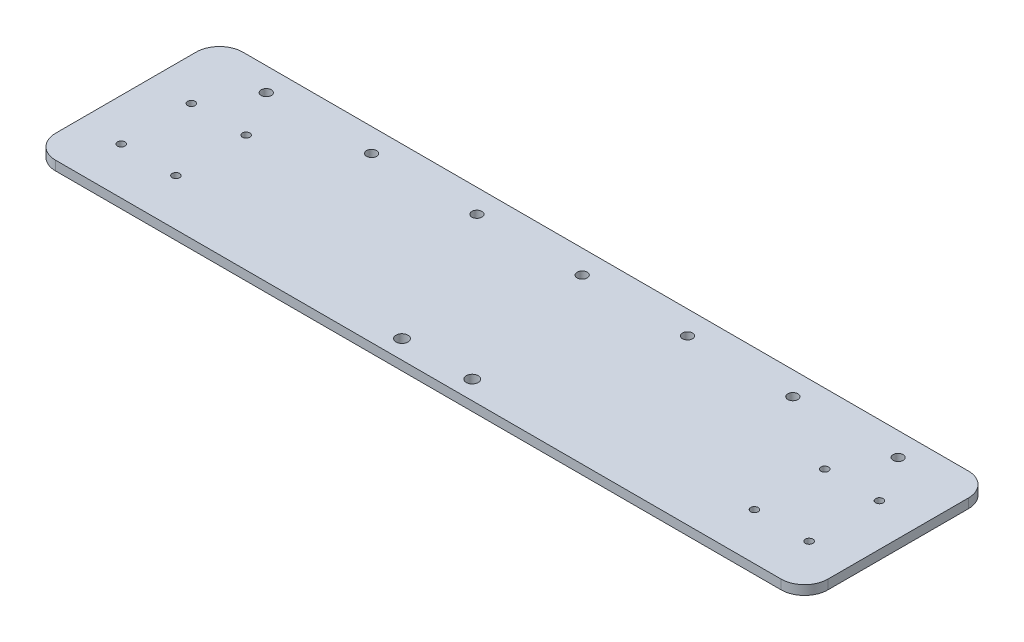
SolidWorks part; units mm, degrees
material "1060 合金"
ref_plane "前视基准面" through (0, 0, 0) normal (0, 0, 1) x (1, 0, 0)
ref_plane "上视基准面" through (0, 0, 0) normal (0, 1, 0) x (1, 0, 0)
ref_plane "右视基准面" through (0, 0, 0) normal (1, 0, 0) x (0, 0, -1)
other "Configuration Table"
sketch "草图2" plane through (0, 0, 0) normal (0, 1, 0) x (1, 0, 0)
  line L0 (0, 57.6658) -> (0, -92.3342) construction
  line L1 (165, 40) -> (-165, 40)
  line L2 (165, 40) -> (165, -40)
  line L4 (-165, 40) -> (-165, -40)
  line L5 (165, 40) -> (-165, -40) construction
  line L6 (165, -40) -> (-165, 40) construction
  line L7 (-15, -32) -> (15, -32) construction
  line L13 (-165, -40) -> (165, -40)
  circle A0 centre (-15, -32) radius 2.55
  circle A1 centre (15, -32) radius 2.55
  point P0 (0, 0)
  point P11 (0, -32)
  dimension "D4" = 5.1
  dimension "D1" = 330
  dimension "D2" = 80
  dimension "D3" = 30
  dimension "D5" = 8
extrude "凸台-拉伸1" add sketch "草图2" along normal blind 4
sketch "草图3" plane through (0, 0, 0) normal (0, 1, 0) x (1, 0, 0)
  line L5 (-165, 40) -> (-165, -40) construction
  line L7 (-147, 10) -> (-123.6, 10) construction
  line L8 (-147, 10) -> (-147, -20) construction
  line L9 (-147, -20) -> (-123.6, -20) construction
  line L10 (-123.6, 10) -> (-123.6, -20) construction
  line L11 (-147, 10) -> (-123.6, -20) construction
  line L12 (-147, -20) -> (-123.6, 10) construction
  line L13 (-165, -40) -> (165, -40) construction
  circle A0 centre (-147, 10) radius 1.6
  circle A1 centre (-147, -20) radius 1.6
  circle A2 centre (-123.6, -20) radius 1.6
  circle A3 centre (-123.6, 10) radius 1.6
  point P4 (-135.3, -5)
  dimension "D4" = 3.2
  dimension "D1" = 18
  dimension "D2" = 23.4
  dimension "D3" = 30
  dimension "D5" = 35
extrude "切除-拉伸1" cut sketch "草图3" along normal through all
mirror "镜向1" about plane through (0, 0, 0) normal (1, 0, 0) of "切除-拉伸1"
sketch "草图4" plane through (0, 0, 0) normal (0, 1, 0) x (1, 0, 0)
  line L0 (0, 0) -> (0, 50000) construction
  line L2 (-165, -40) -> (165, -40) construction
  circle A0 centre (0, 30) radius 2.15
  dimension "D1" = 4.3
  dimension "D2" = 70
extrude "切除-拉伸2" cut sketch "草图4" along normal through all
pattern_linear "阵列(线性)1" count 4 spacing 45 along (1, 0, 0) count 4 spacing 45 along (-1, 0, 0) of "切除-拉伸2"
fillet "圆角1" radius 10 4 edges at (165, 2, 40) (165, 2, -40) (-165, 2, 40) (-165, 2, -40)
